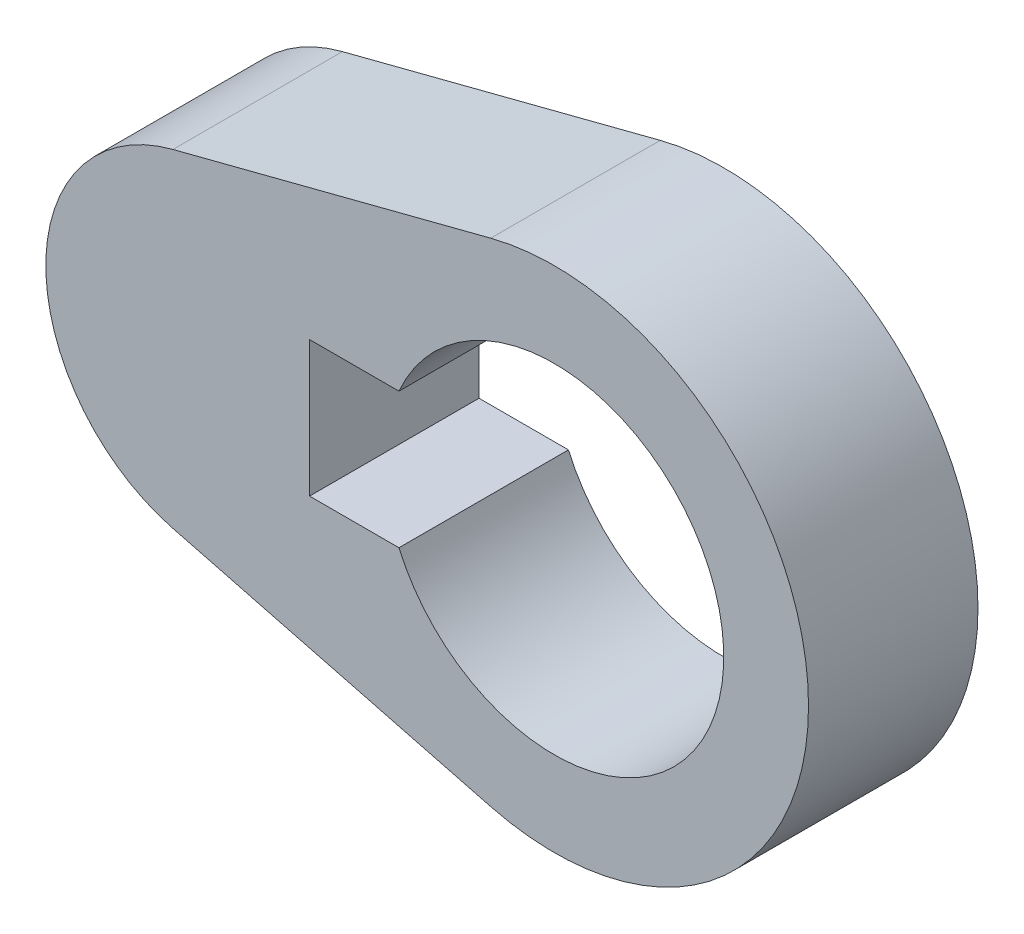
SolidWorks part; units mm, degrees
ref_plane "Front Plane" through (0, 0, 0) normal (0, 0, 1) x (1, 0, 0)
ref_plane "Top Plane" through (0, 0, 0) normal (0, 1, 0) x (1, 0, 0)
ref_plane "Right Plane" through (0, 0, 0) normal (1, 0, 0) x (0, 0, -1)
sketch "Sketch3" plane through (0, 0, 0) normal (0, 0, 1) x (1, 0, 0)
  line L0 (0, 0) -> (-22.5, 0) construction
  line L1 (-18.75, 4.8412) -> (-9.375, 7.2618)
  line L2 (-18.75, -4.8412) -> (-9.375, -7.2618)
  line L4 (-10.28, -2) -> (-14.72, -2)
  line L5 (-10.28, -2) -> (-10.28, 2)
  line L6 (-10.28, 2) -> (-14.72, 2)
  line L7 (-14.72, -2) -> (-14.72, 2)
  line L8 (-10.28, -2) -> (-14.72, 2) construction
  line L9 (-10.28, 2) -> (-14.72, -2) construction
  circle A0 centre (-7.5, 0) radius 7.5
  circle A1 centre (-17.5, 0) radius 5
  circle A2 centre (-7.5, 0) radius 5
  point P12 (-12.5, 0)
  dimension "D2" = 15
  dimension "D3" = 10
  dimension "D4" = 10
  dimension "D1" = 15
  dimension "D5" = 4
  dimension "D6" = 7.22
extrude "Boss-Extrude2" add sketch "Sketch3" along normal blind 5 contours A2 L4 A1 A0 L6 | L6 A1 A0 L4 L7 | A1 L2 A0 | A0 A1 | A1 A0 L1
equation "\"D6@Sketch3\"=5+2.22"
